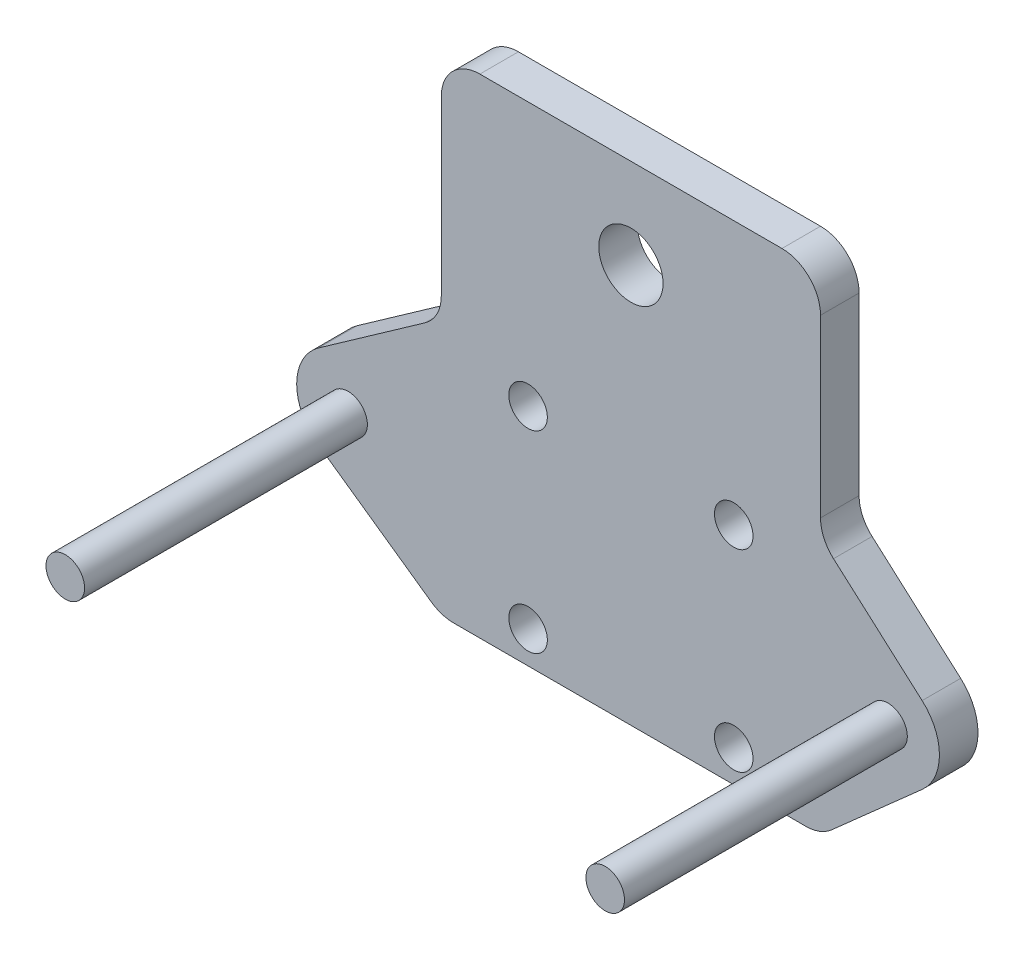
SolidWorks part; units mm, degrees
material "1060 Alloy"
ref_plane "Front Plane" through (0, 0, 0) normal (0, 0, 1) x (1, 0, 0)
ref_plane "Top Plane" through (0, 0, 0) normal (0, 1, 0) x (1, 0, 0)
ref_plane "Right Plane" through (0, 0, 0) normal (1, 0, 0) x (0, 0, -1)
sketch "Sketch2" plane through (0, 0, 0) normal (0, 0, 1) x (1, 0, 0)
  line L0 (-14.75, 7) -> (14.75, 7)
  line L1 (0, -11) -> (0, 0) construction
  line L4 (-14.75, -31) -> (14.75, -31)
  line L7 (-14.75, 7) -> (-14.75, -31)
  line L10 (0, -11) -> (0, -31) construction
  line L12 (14.75, 7) -> (14.75, -31)
  line L16 (-8, -28.5) -> (8, -28.5) construction
  line L17 (-8, -28.5) -> (-8, -13.5) construction
  line L18 (-8, -13.5) -> (8, -13.5) construction
  line L19 (8, -28.5) -> (8, -13.5) construction
  line L20 (-8, -28.5) -> (8, -13.5) construction
  line L21 (-8, -13.5) -> (8, -28.5) construction
  circle A5 centre (-8, -13.5) radius 1.5
  circle A6 centre (8, -13.5) radius 1.5
  circle A7 centre (8, -28.5) radius 1.5
  circle A8 centre (-8, -28.5) radius 1.5
  circle A21 centre (0, 0) radius 2.5
  point P25 (0, -21)
  dimension "D4" = 5
  dimension "D12" = 3
  dimension "D2" = 20
  dimension "D3" = 7
  dimension "D10" = 29.5
  dimension "D11" = 15
  dimension "D13" = 16
  dimension "D5" = 11
extrude "Boss-Extrude1" add sketch "Sketch2" along normal mid plane 3
sketch "Sketch3" plane through (0, 0, 1.5) normal (0, 0, 1) x (1, 0, 0)
  line L0 (-22, -21) -> (20, -21) construction
  line L1 (-8, -13.5) -> (8, -28.5) construction
  line L2 (-24.3036, -24.2701) -> (-14.75, -31)
  line L3 (-24.3036, -17.7299) -> (-14.75, -11)
  line L4 (-14.75, 7) -> (-14.75, -31) construction
  line L5 (0, -31) -> (0, -12.9) construction
  line L6 (-14.75, -31) -> (14.75, -31) construction
  line L7 (22.6535, -23.9931) -> (14.75, -31)
  line L8 (22.6535, -18.0069) -> (14.75, -11)
  line L9 (14.75, -31) -> (14.75, 7) construction
  line L10 (-14.75, -11) -> (-14.75, -31)
  line L11 (14.75, -11) -> (14.75, -31)
  arc A0 (22.6535, -23.9931) -> (22.6535, -18.0069) centre (20, -21) ccw
  arc A1 (-24.3036, -17.7299) -> (-24.3036, -24.2701) centre (-22, -21) ccw
  circle A2 centre (20, -21) radius 1.5
  circle A3 centre (-22, -21) radius 1.5
  point P6 (0, -21)
  point P32 (-1, -21)
  dimension "D1" = 3
  dimension "D2" = 8
  dimension "D3" = 42
  dimension "D4" = 1
extrude "Boss-Extrude2" add sketch "Sketch3" against normal up to surface (3 mm away) up to face at (0, -12, -1.5)
fillet "Fillet2" radius 3 6 edges at (-14.75, 7, 0) (14.75, 7, 0) (14.75, -11, 0) (14.75, -31, 0) (-14.75, -31, 0) (-14.75, -11, 0)
sketch "Sketch4" plane through (0, 0, -1.5) normal (0, 0, -1) x (-1, 0, 0)
  circle A0 centre (22, -21) radius 1.5 construction
  circle A1 centre (-20, -21) radius 1.5 construction
  circle A2 centre (22, -21) radius 1.5
  circle A3 centre (-20, -21) radius 1.5
extrude "Boss-Extrude3" add sketch "Sketch4" against normal blind 25 separate body
